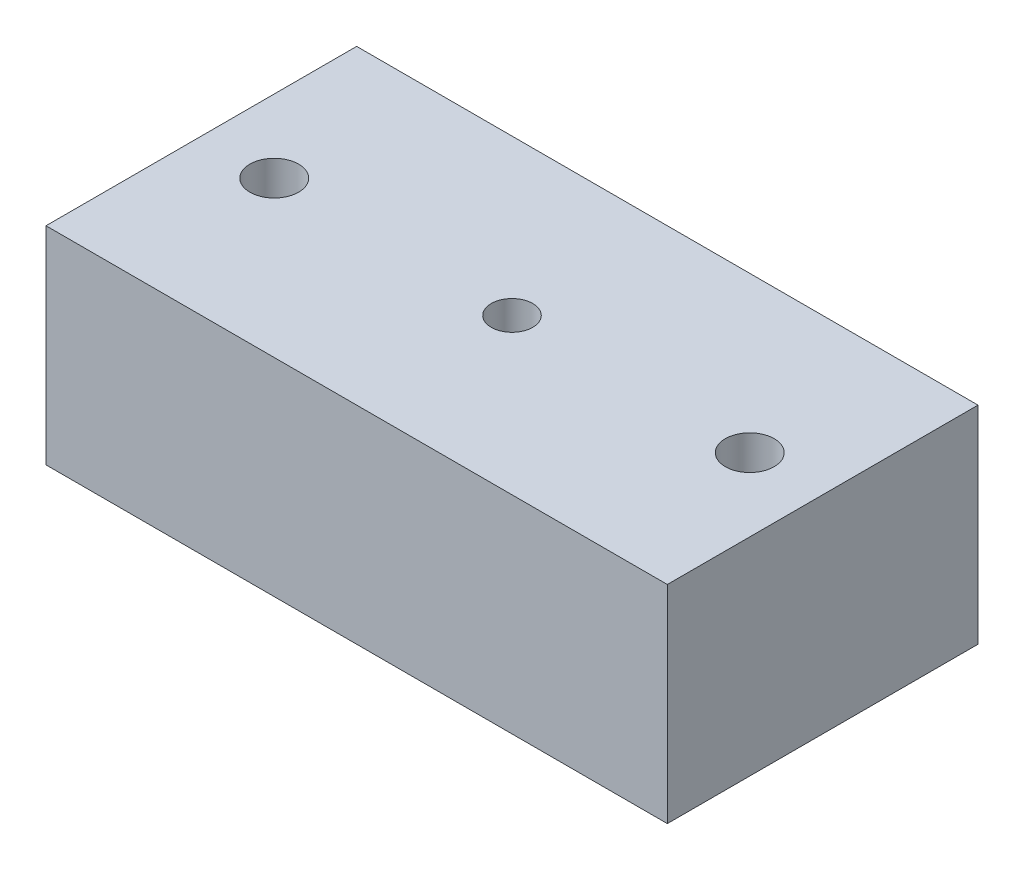
SolidWorks part; units mm, degrees
ref_plane "Front Plane" through (0, 0, 0) normal (0, 0, 1) x (1, 0, 0)
ref_plane "Top Plane" through (0, 0, 0) normal (0, 1, 0) x (1, 0, 0)
ref_plane "Right Plane" through (0, 0, 0) normal (1, 0, 0) x (0, 0, -1)
sketch "Sketch1" plane through (0, 0, 0) normal (0, 1, 0) x (1, 0, 0)
  line L0 (0, 0) -> (0, 18.3183) construction
  line L1 (-60, -30) -> (60, -30)
  line L2 (-60, -30) -> (-60, 30)
  line L3 (-60, 30) -> (60, 30)
  line L4 (60, -30) -> (60, 30)
  line L5 (-60, -30) -> (60, 30) construction
  line L6 (-60, 30) -> (60, -30) construction
  circle A0 centre (0, 0) radius 4
  circle A1 centre (-45.9178, 0) radius 4.7056
  circle A2 centre (45.9178, 0) radius 4.7056
  point P0 (0, 0)
  dimension "D3" = 8
  dimension "D1" = 120
  dimension "D2" = 60
extrude "Boss-Extrude1" add sketch "Sketch1" along normal blind 40
